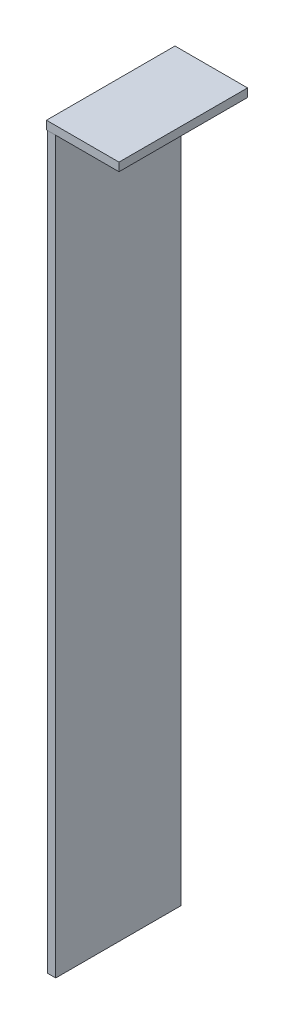
SolidWorks part; units mm, degrees
ref_plane "Front Plane" through (0, 0, 0) normal (0, 0, 1) x (1, 0, 0)
ref_plane "Top Plane" through (0, 0, 0) normal (0, 1, 0) x (1, 0, 0)
ref_plane "Right Plane" through (0, 0, 0) normal (1, 0, 0) x (0, 0, -1)
sketch "Sketch1" plane through (0, 0, 0) normal (1, 0, 0) x (0, 0, -1)
  line L1 (-11.7615, 50.8601) -> (18.2385, 50.8601)
  line L2 (-11.7615, 50.8601) -> (-11.7615, -124.1399)
  line L3 (-11.7615, -124.1399) -> (18.2385, -124.1399)
  line L4 (18.2385, 50.8601) -> (18.2385, -124.1399)
  line L5 (-11.7615, 50.8601) -> (18.2385, -124.1399) construction
  line L6 (-11.7615, -124.1399) -> (18.2385, 50.8601) construction
  point P0 (3.2385, -36.6399)
  point P5 (-11.7615, 50.8601)
  dimension "D1" = 30
  dimension "D2" = 175
extrude "Boss-Extrude1" add sketch "Sketch1" along normal blind 2
sketch "Sketch2" plane through (0, 50.8601, 0) normal (0, 1, 0) x (1, 0, 0)
  line L1 (-0.1626, 18.9824) -> (17.2271, 18.9824)
  line L2 (-0.1626, 18.9824) -> (-0.1626, -11.8258)
  line L3 (-0.1626, -11.8258) -> (17.2271, -11.8258)
  line L4 (17.2271, 18.9824) -> (17.2271, -11.8258)
  line L5 (-0.1626, 18.9824) -> (17.2271, -11.8258) construction
  line L6 (-0.1626, -11.8258) -> (17.2271, 18.9824) construction
  point P0 (8.5322, 3.5783)
  dimension "D1" = 17.3897
extrude "Boss-Extrude3" add sketch "Sketch2" along normal blind 2
